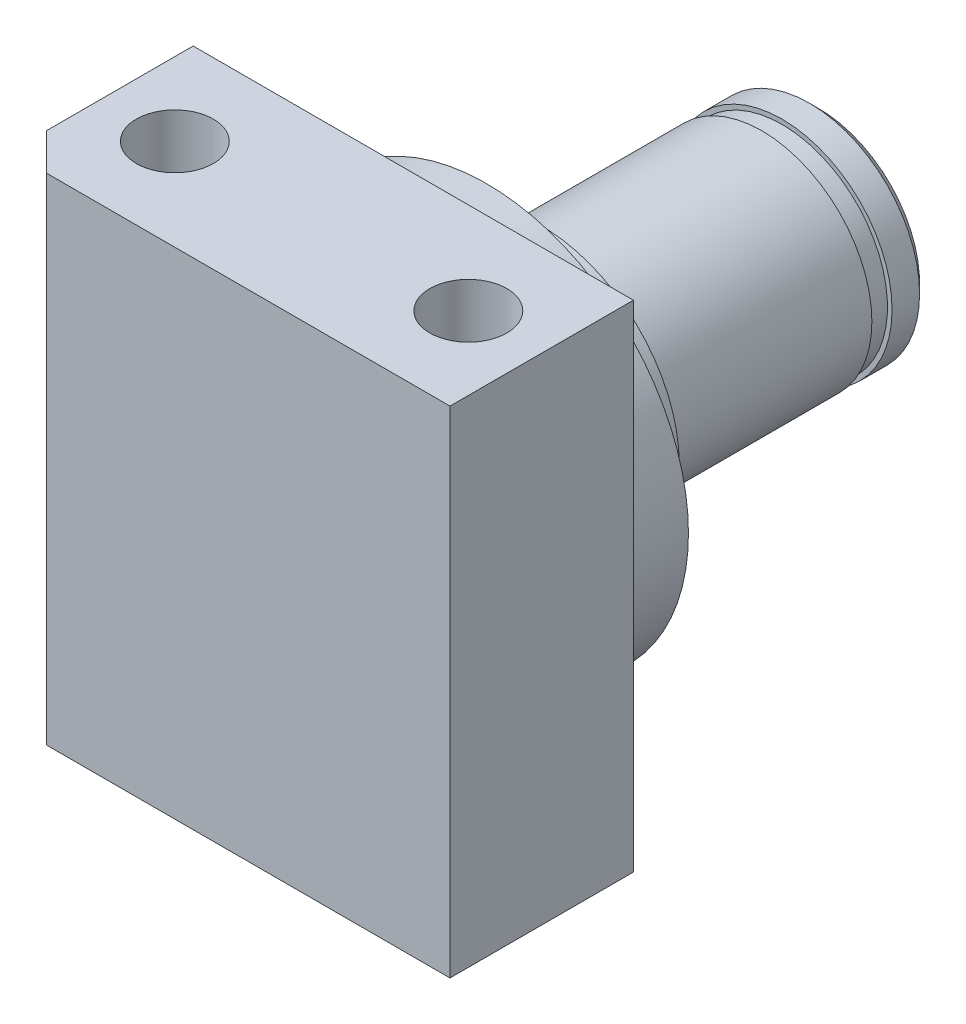
SolidWorks part; units mm, degrees
material "6061-T6 (SS)"
ref_plane "前视基准面" through (0, 0, 0) normal (0, 0, 1) x (1, 0, 0)
ref_plane "上视基准面" through (0, 0, 0) normal (0, 1, 0) x (1, 0, 0)
ref_plane "右视基准面" through (0, 0, 0) normal (1, 0, 0) x (0, 0, -1)
sketch "草图1" plane through (0, 0, 0) normal (0, 0, 1) x (1, 0, 0)
  line L1 (-12, 13.5) -> (12, 13.5)
  line L2 (-12, 13.5) -> (-12, -13.5)
  line L3 (-12, -13.5) -> (12, -13.5)
  line L4 (12, 13.5) -> (12, -13.5)
  line L5 (-12, 13.5) -> (12, -13.5) construction
  line L6 (-12, -13.5) -> (12, 13.5) construction
  point P0 (0, 0)
  dimension "D1" = 24
  dimension "D2" = 27
extrude "凸台-拉伸1" add sketch "草图1" along normal blind 10
sketch "草图2" plane through (0, 0, 0) normal (0, 0, 1) x (1, 0, 0)
  circle A1 centre (0, 0) radius 11
  dimension "D2" = 22
sketch "草图4" plane through (0, 13.5, 0) normal (0, 1, 0) x (1, 0, 0)
  line L0 (-12, -5) -> (12, -5) construction
  line L1 (-12, -10) -> (-12, 0) construction
  line L2 (12, -10) -> (12, 0) construction
  circle A0 centre (-8, -5) radius 2.1
  circle A1 centre (8, -5) radius 2.1
  dimension "D1" = 4.2
  dimension "D2" = 4.2
  dimension "D4" = 4
  dimension "D3" = 4
extrude "切除-拉伸2" cut sketch "草图4" against normal blind 37.0135
extrude "凸台-拉伸2" add sketch "草图2" against normal blind 4
sketch "草图5" plane through (0, 0, -4) normal (0, 0, -1) x (-1, 0, 0)
  circle A0 centre (0, 0) radius 7.5
  dimension "D1" = 15
extrude "凸台-拉伸3" add sketch "草图5" along normal blind 3
sketch "草图6" plane through (0, 0, -7) normal (0, 0, -1) x (-1, 0, 0)
  circle A0 centre (0, 0) radius 5.75
  dimension "D1" = 11.5
extrude "凸台-拉伸4" add sketch "草图6" along normal blind 0.5
sketch "草图7" plane through (0, 0, -7.5) normal (0, 0, -1) x (-1, 0, 0)
  circle A0 centre (0, 0) radius 6
  dimension "D1" = 12
extrude "凸台-拉伸5" add sketch "草图7" along normal blind 11.5
sketch "草图8" plane through (0, 0, -19) normal (0, 0, -1) x (-1, 0, 0)
  circle A0 centre (0, 0) radius 5.75
  dimension "D1" = 11.5
extrude "凸台-拉伸6" add sketch "草图8" along normal blind 1.1
sketch "草图9" plane through (0, 0, -20.1) normal (0, 0, -1) x (-1, 0, 0)
  circle A0 centre (0, 0) radius 6
extrude "凸台-拉伸7" add sketch "草图9" along normal blind 2
chamfer "倒角1" distance 0.5 angle 45 1 edges at (-6, 0, -22.1)
chamfer "倒角2" distance 2 angle 45 1 edges at (-12, 0, 10)
